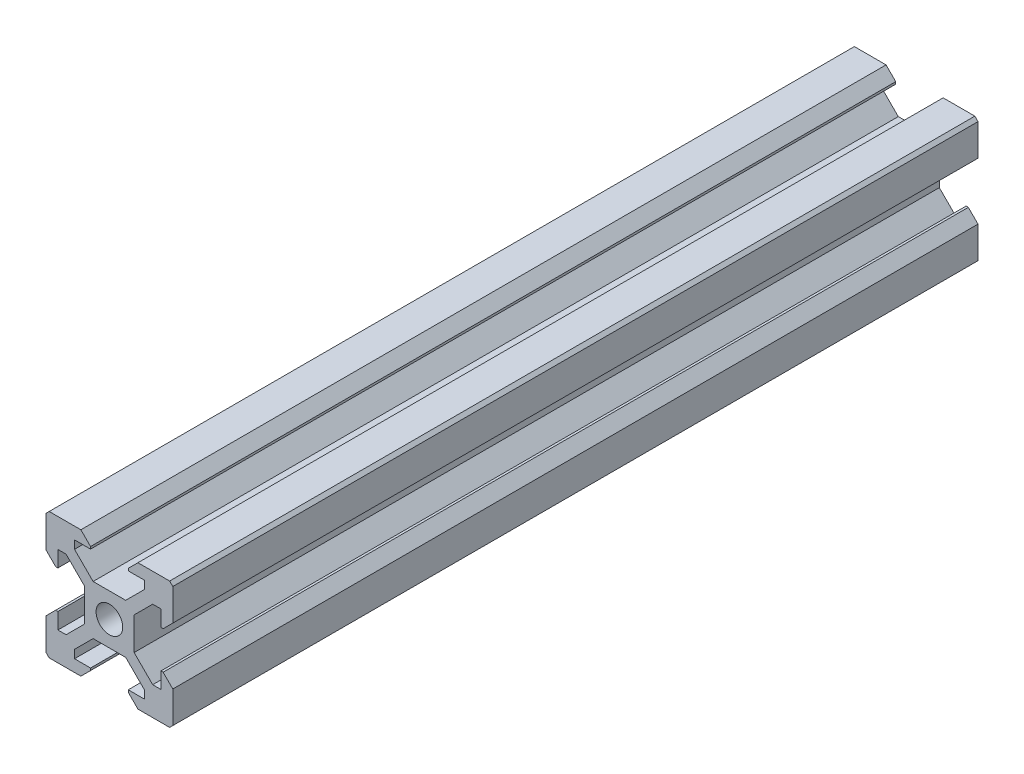
SolidWorks part; units mm, degrees
material "6061 Alloy"
ref_plane "Front Plane" through (0, 0, 0) normal (0, 0, 1) x (1, 0, 0)
ref_plane "Top Plane" through (0, 0, 0) normal (0, 1, 0) x (1, 0, 0)
ref_plane "Right Plane" through (0, 0, 0) normal (1, 0, 0) x (0, 0, -1)
sketch "Sketch1" plane through (0, 0, 0) normal (0, 0, 1) x (1, 0, 0)
  line L0 (15.6876, 55.3211) -> (115.0437, 55.3211) construction
  line L1 (5.5, 6.8294) -> (2.5706, 3.9)
  line L2 (0, 3.9) -> (0, 2.1)
  line L3 (10, 10) -> (1.4849, 1.4849)
  line L4 (10, 10) -> (4.5, 10)
  line L5 (1.4849, 1.4849) -> (3.9, 3.9) construction
  line L6 (10, -10) -> (-10, 10) construction
  line L7 (10, 10) -> (1.4849, 1.4849) construction
  line L8 (0, 0) -> (-10, -10) construction
  line L10 (0, 3.9) -> (2.5706, 3.9)
  line L12 (-3.9, -3.9) -> (0, 0) construction
  line L13 (-3.9, 3.9) -> (3.9, -3.9) construction
  line L14 (5.5, 6.8294) -> (5.5, 8.12)
  line L15 (5.5, 8.12) -> (2.62, 8.12)
  line L16 (2.62, 8.12) -> (4.5, 10)
  line L17 (0, 2.1) -> (0, 16.7618) construction
  arc A0 (1.4849, 1.4849) -> (0, 2.1) centre (0, 0) ccw
  point P2 (0, 0)
  point P7 (0, 0)
  dimension "D3" = 45
  dimension "D4" = 6.1
  dimension "D8" = 4.2
  dimension "D1" = 20
  dimension "D2" = 11
  dimension "D5" = 1.88
  dimension "D6" = 9
  dimension "D7" = 0.94
  dimension "D9" = 3.9
extrude "Boss-Extrude1" add sketch "Sketch1" along normal blind 127
chamfer "Chamfer2" distance 0.5 angle 45 1 edges at (2.62, 8.12, 63.5)
mirror "Mirror1" about plane through (10, 10, 127) normal (-0.7071, 0.7071, 0) of bodies 102
chamfer "Chamfer1" distance 0.5 angle 45 1 edges at (10, 10, 63.5)
mirror "Mirror4" about plane through (0, 3.9, 127) normal (1, 0, 0) of bodies 103 104
mirror "Mirror5" about plane through (-3.9, 0, 127) normal (0, 1, 0) of bodies 105
